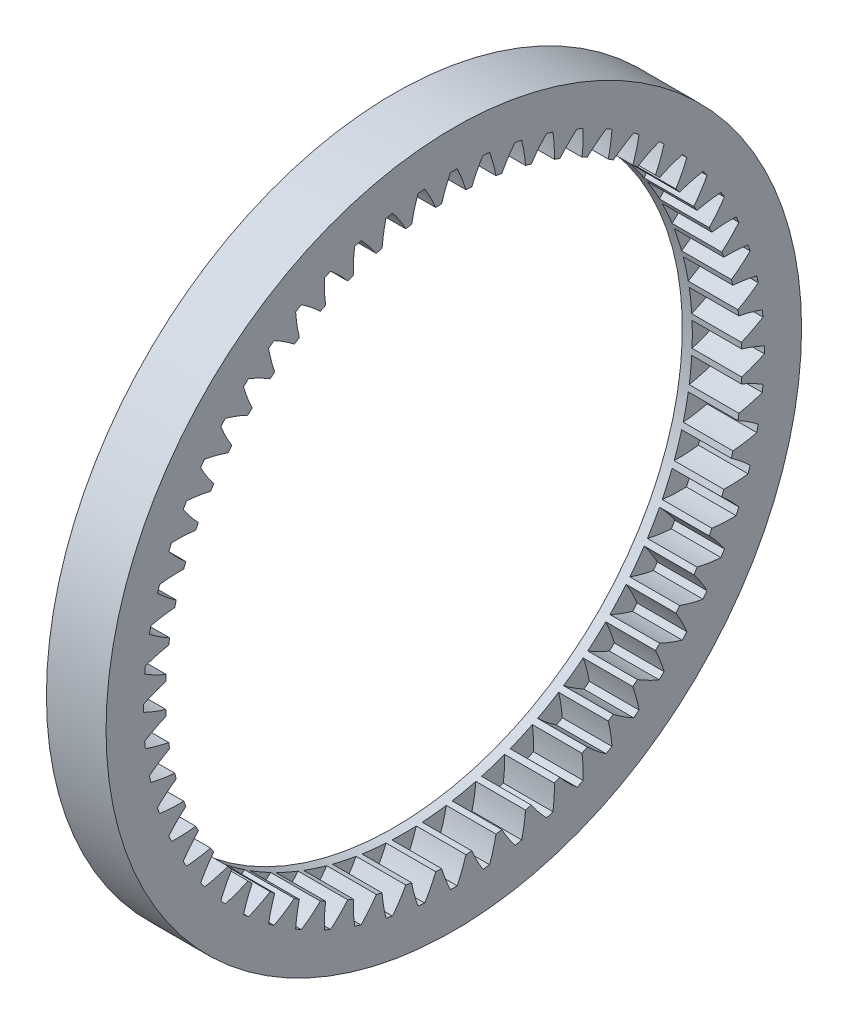
SolidWorks part; units mm, degrees
ref_plane "Plane1" through (0, 0, 0) normal (0, 0, 1) x (1, 0, 0)
ref_plane "Plane2" through (0, 0, 0) normal (0, 1, 0) x (1, 0, 0)
ref_plane "Plane3" through (0, 0, 0) normal (1, 0, 0) x (0, 0, -1)
sketch "HoldingSke" plane through (0, 0, 0) normal (0, 1, 0) x (1, 0, 0)
  line L0 (0, 0) -> (0.5, -0.866)
  line L1 (-15, 0) -> (100, 0) construction
  line L2 (0, 0) -> (-2.1039, 2.3779)
  line L3 (0, 0) -> (-11.863, 4.5341)
  line L4 (0, 0) -> (4.318, 7.479)
  line L5 (0, 0) -> (-23.7986, -8.8762)
  line L6 (0, 0) -> (-10.5278, -7.1032)
  line L7 (-2.1039, 2.3779) -> (3.3635, 27.1825)
  line L8 (-76.2, 3.3779) -> (-54.61, 3.3779)
  line L9 (-71.009, 38.7566) -> (-53.1078, 45.2721)
  line L10 (-76.2, 71.12) -> (104.1128, 71.12)
  line L11 (0, 0) -> (-5, 0)
  line L12 (-76.2, 101.6) -> (-76.162, 101.6)
  line L13 (24.9733, 27.94) -> (52.9518, 28.4284)
  line L14 (24.9733, 27.94) -> (24.9743, 27.94)
  line L15 (24.9733, 27.94) -> (100.4006, 29.5858)
  circle A0 centre (0, 0) radius 35
  circle A1 centre (0, 0) radius 12.7
  circle A2 centre (0, 0) radius 12.7
  dimension "MHD" = 25.4
  dimension "Hub_dia" = 25.4
  dimension "Diameter" = 70
  dimension "Num_teeth" = 60
  dimension "Pitch" = 1
  dimension "Overall_len" = 25.4
  dimension "Show_teeth" = 60
  dimension "Thickness" = 12.7
  dimension "OAL" = 25.4001
  dimension "T_dim" = 21.59
  dimension "Ap" = 20
  dimension "H" = 19.05
  dimension "Pitch_radius" = 180.3128
  dimension "Width" = 5
  dimension "Backlash" = 0.038
  dimension "Addendum_fac" = 1
  dimension "Dedendum_fac" = 1.25
  dimension "Clearance_fac" = 0.25
  dimension "Dedendum_add" = 0.001
  dimension "Module" = 1
sketch "BasProSke" plane through (0, 0, 0) normal (0, 1, 0) x (1, 0, 0)
  line L0 (-10, 0) -> (60, 0) construction
  line L1 (0, 29) -> (0, 35)
  line L2 (0, 29) -> (5, 29)
  line L3 (5, 29) -> (5, 35)
  line L4 (5, 35) -> (0, 35)
  dimension "Diameter" = 70
  dimension "Thickness" = 5
  dimension "Inside_diameter" = 58
revolve "Base-Revolve" add sketch "BasProSke" angle 360 about L0
sketch "TooCutSke" plane through (0, 0, 0) normal (1, 0, 0) x (0, 0, -1)
  line L3 (0.8803, 29.9871) -> (0.8803, 53.6633) construction
  line L4 (0, 0) -> (0, 59.563) construction
  line L5 (0, 0) -> (-3.576, 68.2339) construction
  line L6 (-13.1633, 24.7167) -> (36.4631, 27.3175) construction
  circle A0 centre (0, 0) radius 30 construction
  circle A1 centre (0, 0) radius 31.251 construction
  circle A2 centre (0, 0) radius 25.3717 construction
  circle A3 centre (0, 0) radius 28.9746 construction
  arc A4 (1.2274, 28.9486) -> (0.3395, 31.2492) centre (-13.1633, 24.7167) ccw
  arc A5 (1.2274, 28.9486) -> (-1.2274, 28.9486) centre (0, 0) ccw
  arc A6 (0.3395, 31.2492) -> (-0.3395, 31.2492) centre (0, 0) ccw
  arc A7 (-0.3395, 31.2492) -> (-1.2274, 28.9486) centre (13.1633, 24.7167) ccw
  dimension "Pitch_dia" = 60
  dimension "Base_dia" = 50.7434
  dimension "Root_dia" = 62.502
  dimension "Overcut_dia" = 57.9492
  dimension "Flank_rad" = 15
  dimension "Half_ang" = 3
  dimension "Half_CT" = 0.8803
extrude "ToothCut" cut sketch "TooCutSke" along normal through all
fillet "Breaks" [suppressed] radius 0.1
fillet "RootFillets" [suppressed] radius 0.251
pattern_circular "TeethCuts" count 60 every 6 about axis through (-10, 0, 0) along (1, 0, 0) of "RootFillets", "Breaks", "ToothCut"
sketch "Croquis1" plane through (0, 0, 0) normal (-1, 0, 0) x (0, 0, 1)
  circle A0 centre (0, 0) radius 35
  circle A1 centre (0, 0) radius 29
extrude "Saliente-Extruir1" add sketch "Croquis1" along normal blind 1
equation "' \"Module@HoldingSke\" = 6.35"
equation "' \"Num_teeth@HoldingSke\" = 24"
equation "' \"Ap@HoldingSke\" =  14.5"
equation "' \"Ap@HoldingSke\" = 14.5"
equation "' \"Width@HoldingSke\" = 12"
equation "' \"Diameter@HoldingSke\" = 8 * 25.4"
equation "' \"Show_teeth@HoldingSke\" = 100"
equation "' \"Backlash@HoldingSke\" = 0.009 * 25.4"
equation "' \"Addendum_fac@HoldingSke\" = 1.0"
equation "' \"Dedendum_fac@HoldingSke\" = 1.25"
equation "' \"Dedendum_add@HoldingSke\" = 0.00005 * 25.4"
equation "' \"Clearance_fac@HoldingSke\" = 0.25"
equation "\"Pitch@HoldingSke\" = 1 / \"Module@HoldingSke\" "
equation "\"Overcut_dia@TooCutSke\" = (\"Num_teeth@HoldingSke\" - 2 * \"Addendum_fac@HoldingSke\") / \"Pitch@HoldingSke\" - 0.002 * 25.4"
equation "\"Pitch_dia@TooCutSke\" = \"Num_teeth@HoldingSke\" / \"Pitch@HoldingSke\""
equation "\"Base_dia@TooCutSke\" = \"Num_teeth@HoldingSke\" / \"Pitch@HoldingSke\" * cos((\"Ap@HoldingSke\"  * 3.14159265 / 180)) * 0.90"
equation "\"Root_dia@TooCutSke\" = \"Num_teeth@HoldingSke\"  / \"Pitch@HoldingSke\" + 2 *  \"Dedendum_fac@HoldingSke\"/ \"Pitch@HoldingSke\" + \"Dedendum_add@HoldingSke\" * 2"
equation "\"Half_ang@TooCutSke\" = 180 / \"Num_teeth@HoldingSke\""
equation "\"Half_CT@TooCutSke\" = \"Num_teeth@HoldingSke\" / \"Pitch@HoldingSke\" * sin((3.14159265 / 2 / \"Num_teeth@HoldingSke\")) / 2 + 10 * \"Backlash@HoldingSke\" / 4"
equation "\"Flank_rad@TooCutSke\" = \"Num_teeth@HoldingSke\" / \"Pitch@HoldingSke\" / 4"
equation "\"Radius@RootFillets\"= \"Clearance_fac@HoldingSke\" / \"Pitch@HoldingSke\" + \"Dedendum_add@HoldingSke\""
equation "\"Break_rad@Breaks\" = 0.02 / \"Pitch@HoldingSke\" * 5"
equation "\"Num_teeth@TeethCuts\" = int( \"Show_teeth@HoldingSke\" ) + 1"
equation "\"Num_teeth@TeethCuts\" = ((sgn( \"Num_teeth@TeethCuts\" - \"Num_teeth@HoldingSke\" )-1)*( \"Num_teeth@TeethCuts\" - \"Num_teeth@HoldingSke\" ))/-2+ \"Num_teeth@HoldingSke\""
equation "\"Num_teeth@TeethCuts\" = ((sgn( \"Num_teeth@TeethCuts\" - 2.0)+1)*( \"Num_teeth@TeethCuts\" - 2.0))/2 +2.0"
equation "\"Angle@TeethCuts\" = 360.0 / \"Num_teeth@HoldingSke\""
equation "\"Diameter@BasProSke\" = \"Num_teeth@HoldingSke\"  / \"Pitch@HoldingSke\" + 2 *  \"Dedendum_fac@HoldingSke\"/ \"Pitch@HoldingSke\" + \"Dedendum_add@HoldingSke\" * 2 + 0.002 * 25.4"
equation "\"Diameter@BasProSke\" = ((sgn( \"Diameter@BasProSke\"  - \"Diameter@HoldingSke\" )+1)*( \"Diameter@BasProSke\"  - \"Diameter@HoldingSke\" ))/2 + \"Diameter@HoldingSke\""
equation "\"Inside_diameter@BasProSke\" =  (\"Num_teeth@HoldingSke\" - 2 * \"Addendum_fac@HoldingSke\") / \"Pitch@HoldingSke\" "
equation "\"Thickness@BasProSke\"  = \"Width@HoldingSke\""
